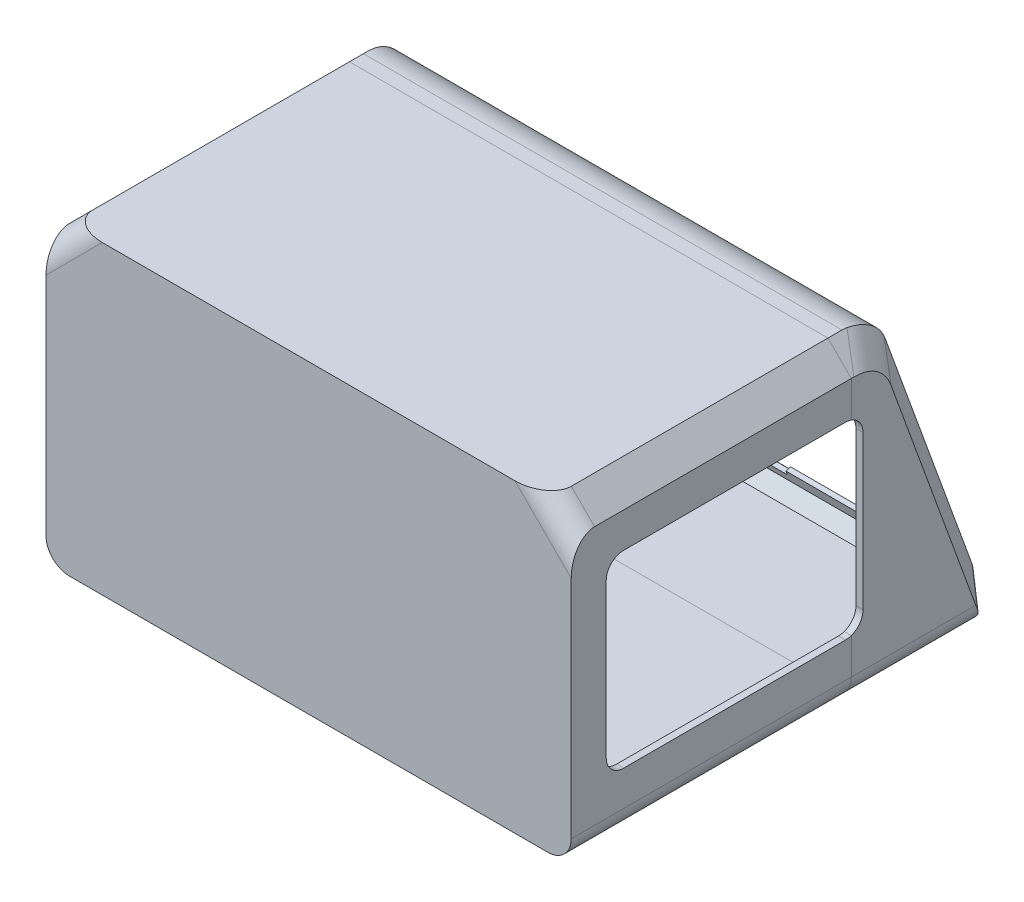
SolidWorks part; units mm, degrees
ref_plane "Front Plane" through (0, 0, 0) normal (0, 0, 1) x (1, 0, 0)
ref_plane "Top Plane" through (0, 0, 0) normal (0, 1, 0) x (1, 0, 0)
ref_plane "Right Plane" through (0, 0, 0) normal (1, 0, 0) x (0, 0, -1)
sketch "Sketch1" plane through (0, 0, 0) normal (0, 0, 1) x (1, 0, 0)
  line L0 (-89.5, -65.4) -> (89.5, -65.4)
  line L1 (106.5, -48.4) -> (106.5, 48.4)
  line L2 (89.5, 65.4) -> (-89.5, 65.4)
  line L3 (-106.5, 48.4) -> (-106.5, -48.4)
  line L4 (-89.5, -55.4) -> (89.5, -55.4)
  line L5 (96.5, -48.4) -> (96.5, 48.4)
  line L6 (89.5, 55.4) -> (-89.5, 55.4)
  line L7 (-96.5, 48.4) -> (-96.5, -48.4)
  line L8 (-89.5, -55.4) -> (89.5, -55.4) construction
  line L9 (96.5, -48.4) -> (96.5, 48.4) construction
  line L10 (89.5, 55.4) -> (-89.5, 55.4) construction
  line L11 (-96.5, 48.4) -> (-96.5, -48.4) construction
  line L13 (118.5, -65.4) -> (-106.5, -65.4)
  line L14 (118.5, -65.4) -> (118.5, 65.4)
  line L15 (118.5, 65.4) -> (-106.5, 65.4)
  line L16 (-106.5, -65.4) -> (-106.5, 65.4)
  arc A0 (89.5, -65.4) -> (106.5, -48.4) centre (89.5, -48.4) ccw construction
  arc A1 (106.5, 48.4) -> (89.5, 65.4) centre (89.5, 48.4) ccw construction
  arc A2 (-89.5, 65.4) -> (-106.5, 48.4) centre (-89.5, 48.4) ccw construction
  arc A3 (-106.5, -48.4) -> (-89.5, -65.4) centre (-89.5, -48.4) ccw construction
  arc A4 (89.5, -55.4) -> (96.5, -48.4) centre (89.5, -48.4) ccw
  arc A5 (96.5, 48.4) -> (89.5, 55.4) centre (89.5, 48.4) ccw
  arc A6 (-89.5, 55.4) -> (-96.5, 48.4) centre (-89.5, 48.4) ccw
  arc A7 (-96.5, -48.4) -> (-89.5, -55.4) centre (-89.5, -48.4) ccw
  arc A8 (89.5, -55.4) -> (96.5, -48.4) centre (89.5, -48.4) ccw construction
  arc A9 (96.5, 48.4) -> (89.5, 55.4) centre (89.5, 48.4) ccw construction
  arc A10 (-89.5, 55.4) -> (-96.5, 48.4) centre (-89.5, 48.4) ccw construction
  arc A11 (-96.5, -48.4) -> (-89.5, -55.4) centre (-89.5, -48.4) ccw construction
  point P24 (118.5, -65.4)
  point P25 (-106.5, 65.4)
  dimension "D3" = 225
  dimension "D1" = 0
  dimension "D2" = 10
extrude "Boss-Extrude1" add sketch "Sketch1" along normal blind 140 contours L14 L13 L16 L15
sketch "Sketch2" plane through (-106.5, 0, 0) normal (-1, 0, 0) x (0, 0, 1)
  line L0 (0, -65.4) -> (-47.6073, -65.4)
  line L1 (-47.6073, -65.4) -> (0, 65.4)
  line L2 (0, -65.4) -> (0, 65.4) construction
  line L3 (0, -65.4) -> (0, 65.4)
  line L7 (0, 65.4) -> (0, -65.4)
  line L8 (0, -65.4) -> (140, -65.4)
  line L9 (140, -65.4) -> (140, 65.4)
  line L10 (140, 65.4) -> (0, 65.4)
  line L12 (0, -65.4) -> (140, -65.4)
  line L13 (140, -65.4) -> (140, 65.4)
  line L14 (140, 65.4) -> (0, 65.4)
  line M7 (0, 65.4) -> (0, -65.4)
  dimension "D1" = 20
  dimension "D2" = 0
extrude "Boss-Extrude2" add sketch "Sketch2" against normal up to surface (225 mm away) contours L1 L0 M7 up to face at (118.5, 0, 70)
chamfer "Chamfer1" distance 10 angle 45 4 edges at (-106.5, 0, -23.8037) (-106.5, 65.4, 70) (118.5, 0, -23.8037) (118.5, 65.4, 70)
fillet "Fillet1" radius 10 2 edges at (-101.5, 60.4, 140) (113.5, 60.4, 140)
fillet "Fillet2" radius 20 1 edges at (6, 65.4, 0)
fillet "Fillet3" radius 24 2 edges at (-103.3085, 58.5915, 4.7673) (115.3085, 58.5915, 4.7673)
chamfer "Chamfer2" distance 10 angle 45 1 edges at (6, -65.4, -47.6073)
fillet "Fillet4" radius 12.5 2 edges at (113.1985, -61.7342, -41.2731) (-101.1985, -61.7342, -41.2731)
fillet "Fillet5" radius 10 2 edges at (-106.5, -65.4, 53.1269) (118.5, -65.4, 53.1269)
shell "Shell1" thickness 3
sketch "Sketch3" plane through (118.5, 0, 0) normal (1, 0, 0) x (0, 0, -1)
  line L0 (-140, -55.4) -> (-140, 41.2579) construction
  line L1 (-15, 40.4) -> (-140, 40.4)
  line L2 (-15, 40.4) -> (-15, -40.4)
  line L3 (-15, -40.4) -> (-140, -40.4)
  line L4 (-140, 40.4) -> (-140, -40.4)
  line L5 (-18.885, 55.4) -> (-130, 55.4) construction
  line L7 (-140, -55.4) -> (33.3258, -55.4) construction
  line L10 (-15, 40.4) -> (-125, 40.4)
  line L11 (-15, 40.4) -> (-15, -40.4)
  line L12 (-15, -40.4) -> (-125, -40.4)
  line L13 (-125, 40.4) -> (-125, -40.4)
  dimension "D1" = 15
  dimension "D2" = 15
  dimension "D3" = 125
  dimension "D4" = 15
extrude "Cut-Extrude1" cut sketch "Sketch3" against normal blind 3 contours L1 L13 L3 L2
fillet "Fillet6" radius 7.5 4 edges at (117, 40.4, 15) (117, -40.4, 15) (117, -40.4, 125) (117, 40.4, 125)
sketch "Sketch4" plane through (0, 7.6503, -21.0192) normal (0, 0.342, -0.9397) x (-1, 0, 0)
  line L0 (-6, 47.4517) -> (-6, -69.9365) construction
  line L1 (-108.5, -11.2424) -> (96.5, -11.2424) construction
  line L4 (-96.1051, -69.9365) -> (84.1051, -69.9365)
  line L5 (96.5, -60.2659) -> (96.5, 47.4517)
  line L6 (96.5, 47.4517) -> (-108.5, 47.4517)
  line L7 (-108.5, 47.4517) -> (-108.5, -60.2659)
  line L8 (-96.1051, -69.9365) -> (84.1051, -69.9365) construction
  line L9 (96.5, -60.2659) -> (96.5, 47.4517) construction
  line L10 (96.5, 47.4517) -> (-108.5, 47.4517) construction
  line L11 (-108.5, 47.4517) -> (-108.5, -60.2659) construction
  ellipse E2 centre (78.8223, -56.1443) end of major axis (95.6922, -64.0108) minor radius 12.5 (84.1051, -69.9365) -> (96.5, -60.2659) ccw
  ellipse E3 centre (-90.8223, -56.1443) end of major axis (-107.6922, -64.0108) minor radius 12.5 (-108.5, -60.2659) -> (-96.1051, -69.9365) ccw
  ellipse E4 centre (78.8223, -56.1443) end of major axis (95.6922, -64.0108) minor radius 12.5 (84.1051, -69.9365) -> (96.5, -60.2659) ccw construction
  ellipse E5 centre (-90.8223, -56.1443) end of major axis (-107.6922, -64.0108) minor radius 12.5 (-108.5, -60.2659) -> (-96.1051, -69.9365) ccw construction
  point P8 (-6, -11.2424)
  point P13 (-157.331, -25.3999)
  dimension "D1" = 0
sketch "Sketch5" plane through (0, 7.6503, -21.0192) normal (0, 0.342, -0.9397) x (-1, 0, 0)
  line L0 (-95.5, -66.6424) -> (83.5, -66.6424) construction
  line L1 (-95.5, -66.6424) -> (83.5, -66.6424)
  line L2 (83.5, 44.1576) -> (-95.5, 44.1576) construction
  line L3 (83.5, 44.1576) -> (-95.5, 44.1576)
  line L4 (-102.5, 37.1576) -> (-102.5, -59.6424) construction
  line L5 (90.5, -59.6424) -> (90.5, 37.1576) construction
  line L6 (-102.5, 37.1576) -> (-102.5, -59.6424) construction
  line L7 (90.5, -59.6424) -> (90.5, 37.1576) construction
  line L8 (90.85, -59.6424) -> (90.85, 37.1576)
  line L9 (83.5, 44.5076) -> (-95.5, 44.5076)
  line L10 (-102.85, 37.1576) -> (-102.85, -59.6424)
  line L11 (-95.5, -66.9924) -> (83.5, -66.9924)
  arc A0 (-95.5, 44.1576) -> (-102.5, 37.1576) centre (-95.5, 37.1576) ccw construction
  arc A1 (-102.5, -59.6424) -> (-95.5, -66.6424) centre (-95.5, -59.6424) ccw construction
  arc A2 (83.5, -66.6424) -> (90.5, -59.6424) centre (83.5, -59.6424) ccw construction
  arc A3 (90.5, 37.1576) -> (83.5, 44.1576) centre (83.5, 37.1576) ccw construction
  arc A4 (-95.5, 44.1576) -> (-102.5, 37.1576) centre (-95.5, 37.1576) ccw
  arc A5 (-102.5, -59.6424) -> (-95.5, -66.6424) centre (-95.5, -59.6424) ccw
  arc A6 (83.5, -66.6424) -> (90.5, -59.6424) centre (83.5, -59.6424) ccw
  arc A7 (90.5, 37.1576) -> (83.5, 44.1576) centre (83.5, 37.1576) ccw
  arc A8 (90.85, 37.1576) -> (83.5, 44.5076) centre (83.5, 37.1576) ccw
  arc A9 (-95.5, 44.5076) -> (-102.85, 37.1576) centre (-95.5, 37.1576) ccw
  arc A10 (-102.85, -59.6424) -> (-95.5, -66.9924) centre (-95.5, -59.6424) ccw
  arc A11 (83.5, -66.9924) -> (90.85, -59.6424) centre (83.5, -59.6424) ccw
  point P2 (-95.5, 37.1576)
  dimension "D1" = 0.35
extrude "Cut-Extrude2" cut sketch "Sketch5" against normal blind 1
sketch "Sketch6" plane through (0, 6.6243, -18.2001) normal (0, -0.342, 0.9397) x (1, 0, 0)
  line L0 (30.7, -61.9924) -> (-22.3, -61.9924) construction
  line L1 (-22.3, -62.8424) -> (-77.9, -62.8424) construction
  line L2 (-78.9, -61.8424) -> (-78.9, 36.8576) construction
  line L3 (86.4, -62.8424) -> (30.7, -62.8424) construction
  line L4 (-77.9, 37.8576) -> (86.4, 37.8576) construction
  line L5 (87.4, 36.8576) -> (87.4, -61.8424) construction
  line L6 (30.7, -61.9924) -> (-22.3, -61.9924)
  line L7 (-22.3, -62.8424) -> (-77.9, -62.8424)
  line L8 (-78.9, -61.8424) -> (-78.9, 36.8576)
  line L9 (86.4, -62.8424) -> (30.7, -62.8424) construction
  line L10 (-77.9, 37.8576) -> (86.4, 37.8576) construction
  line L11 (87.4, 36.8576) -> (87.4, -61.8424) construction
  line L12 (87.75, 38.2076) -> (-79.25, 38.2076)
  line L13 (87.4, 37.8576) -> (-78.9, 37.8576) construction
  line L14 (87.4, 37.8576) -> (87.4, -62.8424) construction
  line L15 (87.4, -62.8424) -> (-78.9, -62.8424)
  line L16 (-78.9, 37.8576) -> (-78.9, -62.8424)
  line L17 (30.7, -61.9924) -> (-22.3, -61.9924)
  line L18 (30.7, -61.9924) -> (30.7, -64.9924)
  line L19 (30.7, -64.9924) -> (-22.3, -64.9924)
  line L20 (-22.3, -61.9924) -> (-22.3, -64.9924)
  line L21 (-79.25, 38.2076) -> (-79.25, -63.1924)
  line L22 (87.75, -63.1924) -> (-79.25, -63.1924)
  line L23 (87.75, 38.2076) -> (87.75, -63.1924)
  point P12 (87.4, 37.8576)
  point P13 (-78.9, -62.8424)
  dimension "D1" = 3
  dimension "D2" = 0.35
extrude "Cut-Extrude3" cut sketch "Sketch6" against normal up to next
ref_plane "Plane1" through (0, 0, 20) normal (0, 0, 1) x (1, 0, 0)
split "Split1" trim tools "Plane1" bodies to split 105 resulting bodies 107 108
